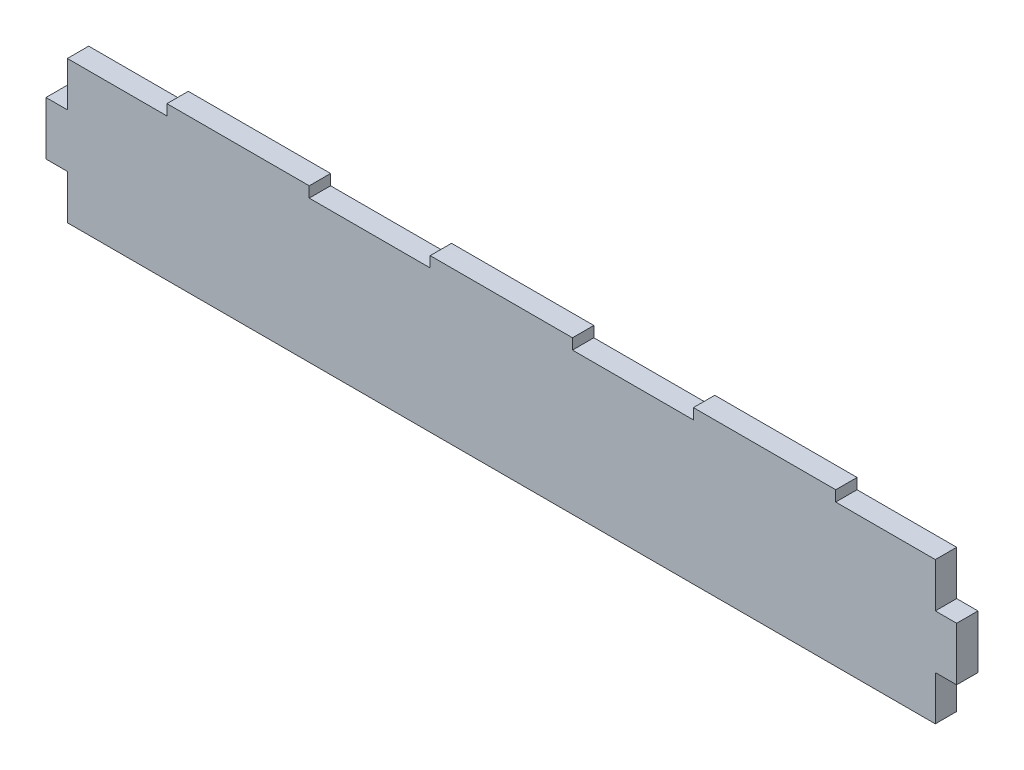
SolidWorks part; units mm, degrees
ref_plane "Спереди" through (0, 0, 0) normal (0, 0, 1) x (1, 0, 0)
ref_plane "Сверху" through (0, 0, 0) normal (0, 1, 0) x (1, 0, 0)
ref_plane "Справа" through (0, 0, 0) normal (1, 0, 0) x (0, 0, -1)
sketch "Эскиз2" plane through (0, 0, 0) normal (0, 0, 1) x (1, 0, 0)
  line L0 (68, 40) -> (102, 40)
  line L1 (0, 0) -> (244, 0)
  line L2 (0, 0) -> (0, 12.5)
  line L3 (0, 40) -> (28, 40)
  line L4 (244, 0) -> (244, 12.5)
  line L5 (0, 27.5) -> (-6, 27.5)
  line L7 (0, 12.5) -> (-6, 12.5)
  line L8 (-6, 27.5) -> (-6, 12.5)
  line L9 (244, 27.5) -> (250, 27.5)
  line L11 (244, 12.5) -> (250, 12.5)
  line L12 (250, 27.5) -> (250, 12.5)
  line L14 (28, 40) -> (28, 43)
  line L15 (28, 43) -> (68, 43)
  line L16 (68, 40) -> (68, 43)
  line L18 (102, 40) -> (102, 43)
  line L19 (102, 43) -> (142, 43)
  line L20 (142, 40) -> (142, 43)
  line L22 (176, 40) -> (176, 43)
  line L23 (176, 43) -> (216, 43)
  line L24 (216, 40) -> (216, 43)
  line L25 (142, 40) -> (176, 40)
  line L26 (216, 40) -> (244, 40)
  line L27 (244, 27.5) -> (244, 40)
  line L28 (0, 27.5) -> (0, 40)
  dimension "D1" = 40
  dimension "D2" = 244
  dimension "D3" = 40
  dimension "D4" = 40
  dimension "D5" = 40
  dimension "D6" = 3
  dimension "D7" = 28
  dimension "D8" = 34
  dimension "D9" = 34
  dimension "D10" = 6
  dimension "D11" = 6
  dimension "D12" = 15
  dimension "D13" = 12.5
extrude "Бобышка-Вытянуть1" add sketch "Эскиз2" along normal blind 6
